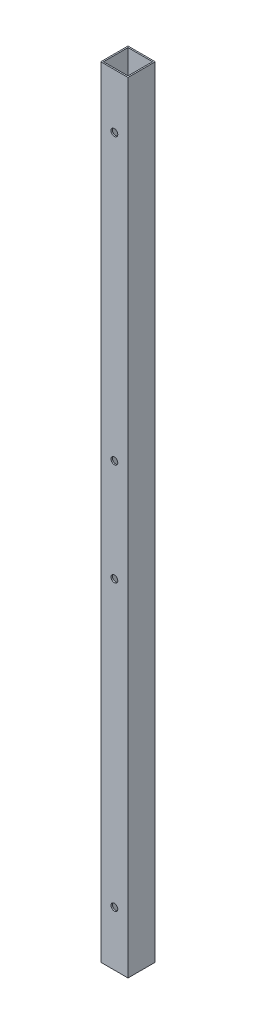
SolidWorks part; units mm, degrees
material "Alloy Steel"
ref_plane "Front Plane" through (0, 0, 0) normal (0, 0, 1) x (1, 0, 0)
ref_plane "Top Plane" through (0, 0, 0) normal (0, 1, 0) x (1, 0, 0)
ref_plane "Right Plane" through (0, 0, 0) normal (1, 0, 0) x (0, 0, -1)
sketch "Sketch2" plane through (0, 0, 0) normal (0, 1, 0) x (1, 0, 0)
  line L0 (-22.86, 22.86) -> (22.86, 22.86)
  line L1 (-25.4, 25.4) -> (25.4, 25.4)
  line L2 (-25.4, 25.4) -> (-25.4, -25.4)
  line L3 (-25.4, -25.4) -> (25.4, -25.4)
  line L4 (25.4, 25.4) -> (25.4, -25.4)
  line L5 (-25.4, 25.4) -> (25.4, -25.4) construction
  line L6 (-25.4, -25.4) -> (25.4, 25.4) construction
  line L7 (22.86, 22.86) -> (22.86, -22.86)
  line L8 (-22.86, -22.86) -> (22.86, -22.86)
  line L9 (-22.86, 22.86) -> (-22.86, -22.86)
  point P0 (0, 0)
  dimension "D1" = 50.8
  dimension "D2" = 50.8
  dimension "D3" = 2.54
extrude "Boss-Extrude2" add sketch "Sketch2" along normal blind 1454.15
hole_wizard "#97 (0.5) Diameter Hole1" positions "3DSketch2" profile "Sketch4" hole size "#97" standard "ANSI Inch" end condition through all
sketch3d "3DSketch2"
  line L0 (-25.4, 1454.15, 25.4) -> (-25.4, 0, 25.4) construction
  line L1 (-25.4, 0, 25.4) -> (25.4, 0, 25.4) construction
  line L2 (-25.4, 1454.15, 25.4) -> (25.4, 1454.15, 25.4) construction
  point P0 (0, 1352.55, 25.4)
  point P2 (0, 101.6, 25.4)
  dimension "D1" = 25.4
  dimension "D2" = 25.4
  dimension "D3" = 101.6
  dimension "D4" = 101.6
sketch "Sketch4" plane through (0, 1352.55, 25.4) normal (1, 0, 0) x (0, -1, 0)
  line L0 (0, 0) -> (0, 50.8)
  line L1 (0, 50.8) -> (6.35, 50.8)
  line L2 (6.35, 50.8) -> (6.35, 0)
  line L5 (6.35, 0) -> (0, 0)
  line L11 (0, -6.35) -> (0, 107.95) construction
  dimension "Thru Hole Dia." = 12.7
  dimension "Thru Hole Depth" = 50.8
sketch "Sketch5" plane through (0, 0, 25.4) normal (0, 0, 1) x (1, 0, 0)
  line L0 (-226.1228, 727.075) -> (279.1924, 727.075) construction
  line L1 (-25.4, 1454.15) -> (25.4, 1454.15) construction
  line L2 (-226.1228, 650.875) -> (279.1924, 650.875) construction
  line L3 (-226.1228, 803.275) -> (279.1924, 803.275) construction
  dimension "D1" = 727.075
  dimension "D2" = 76.2
  dimension "D3" = 76.2
hole_wizard "#97 (0.5) Diameter Hole2" positions "3DSketch3" profile "Sketch6" hole size "#97" standard "ANSI Inch" end condition through all
sketch3d "3DSketch3"
  line L0 (-226.1228, 803.275, 25.4) -> (279.1924, 803.275, 25.4) construction
  line L1 (-226.1228, 650.875, 25.4) -> (279.1924, 650.875, 25.4) construction
  line L2 (-25.4, 1454.15, 25.4) -> (-25.4, 0, 25.4) construction
  point P0 (0, 822.325, 25.4)
  point P2 (0, 631.825, 25.4)
  dimension "D1" = 19.05
  dimension "D2" = 19.05
  dimension "D3" = 25.4
  dimension "D4" = 25.4
sketch "Sketch6" plane through (0, 822.325, 25.4) normal (1, 0, 0) x (0, -1, 0)
  line L0 (0, 0) -> (0, 50.8)
  line L1 (0, 50.8) -> (6.35, 50.8)
  line L2 (6.35, 50.8) -> (6.35, 0)
  line L5 (6.35, 0) -> (0, 0)
  line L11 (0, -6.35) -> (0, 107.95) construction
  dimension "Thru Hole Dia." = 12.7
  dimension "Thru Hole Depth" = 50.8
